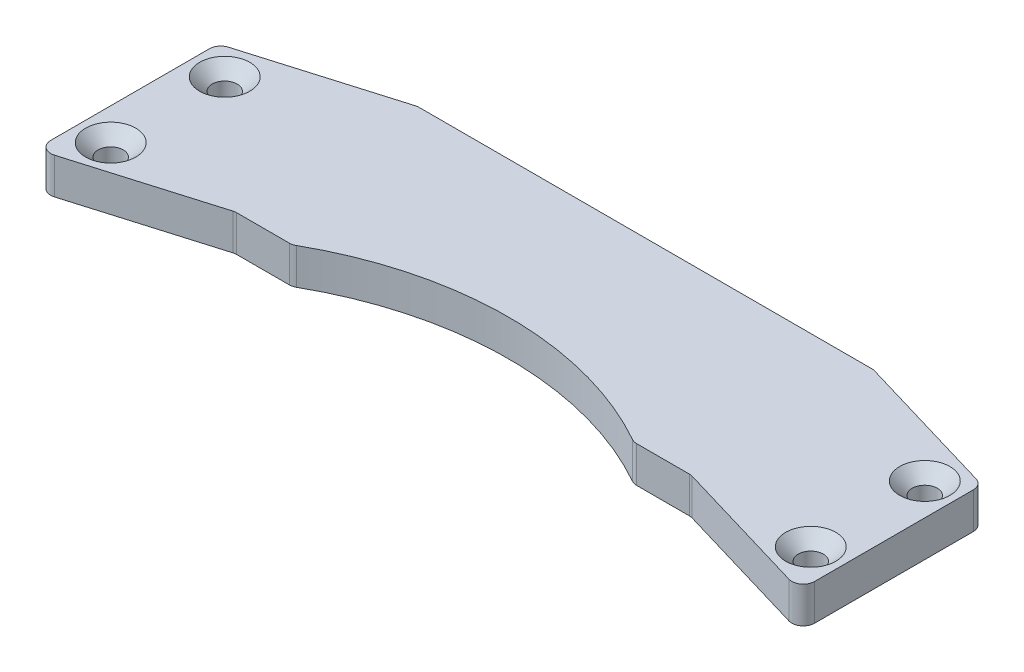
SolidWorks part; units mm, degrees
ref_plane "Front Plane" through (0, 0, 0) normal (0, 0, 1) x (1, 0, 0)
ref_plane "Top Plane" through (0, 0, 0) normal (0, 1, 0) x (1, 0, 0)
ref_plane "Right Plane" through (0, 0, 0) normal (1, 0, 0) x (0, 0, -1)
sketch "Sketch1" plane through (0, 0, 0) normal (0, 1, 0) x (1, 0, 0)
  line L0 (-33.5, 0) -> (-33.5, 16)
  line L9 (-33.5, 0) -> (-20, 4)
  line L19 (0, 0) -> (-33.5, 0) construction
  line L20 (-33.5, 16) -> (-20, 20)
  line L21 (-20, 20) -> (0, 20)
  line L22 (0, 20) -> (0, 0) construction
  line L24 (-20, 4) -> (0, 4)
  line L25 (0, 4) -> (0, 20)
  point P0 (0, 0)
  dimension "D1" = 33.5
  dimension "D2" = 20
  dimension "D3" = 16
  dimension "D4" = 20
extrude "Boss-Extrude1" add sketch "Sketch1" along normal blind 3.175
hole_wizard "CSK for M2 Flat Head Machine Screw1" positions "Sketch2" profile "Sketch3" countersink size "M2" standard "ANSI Metric" end condition through all
sketch "Sketch2" plane through (0, 3.175, 0) normal (0, 1, 0) x (1, 0, 0)
  line L9 (-30.7, 3.8) -> (-30.7, 13.8) construction
  line L10 (-33.5, 16) -> (-33.5, 0) construction
  point P79 (-30.7, 13.8)
  point P81 (-30.7, 3.8)
  dimension "D1" = 10
  dimension "D2" = 2.8
  dimension "D3" = 3.8
sketch "Sketch3" plane through (-30.7, 3.175, -13.8) normal (1, 0, 0) x (0, 0, 1)
  line L0 (0, 0) -> (0, 3.175)
  line L1 (0, 3.175) -> (1.1, 3.175)
  line L2 (1.1, 3.175) -> (1.1, 1.1)
  line L3 (1.1, 1.1) -> (2.2, 0)
  line L5 (2.2, 0) -> (0, 0)
  line L6 (-1.1, 1.1) -> (-2.2, 0) construction
  line L11 (0, -6.35) -> (0, 107.95) construction
  dimension "Thru Hole Dia." = 2.2
  dimension "Thru Hole Depth" = 3.175
  dimension "Near C'Sink Dia." = 4.4
  dimension "Near C'Sink Angle" = 90
mirror "Mirror1" about plane through (0, 0, 0) normal (1, 0, 0) of bodies 102
sketch "Sketch5" plane through (0, 3.175, 0) normal (0, 1, 0) x (1, 0, 0)
  line L0 (-20, 4) -> (20, 4) construction
  line L1 (0, -22) -> (0, 0) construction
  circle A0 centre (0, -22) radius 30
  dimension "D2" = 60
  dimension "D1" = 4
extrude "Cut-Extrude2" cut sketch "Sketch5" against normal through all
fillet "Fillet1" radius 1 10 edges at (-33.5, 1.5875, -16) (-20, 1.5875, -20) (20, 1.5875, -20) (33.5, 1.5875, -16) (33.5, 1.5875, 0) (20, 1.5875, -4) (-20, 1.5875, -4) (-33.5, 1.5875, 0) (14.9666, 1.5875, -4) (-14.9666, 1.5875, -4)
equation "\"D3@Sketch2\"=\"D2@Sketch2\"+1"
